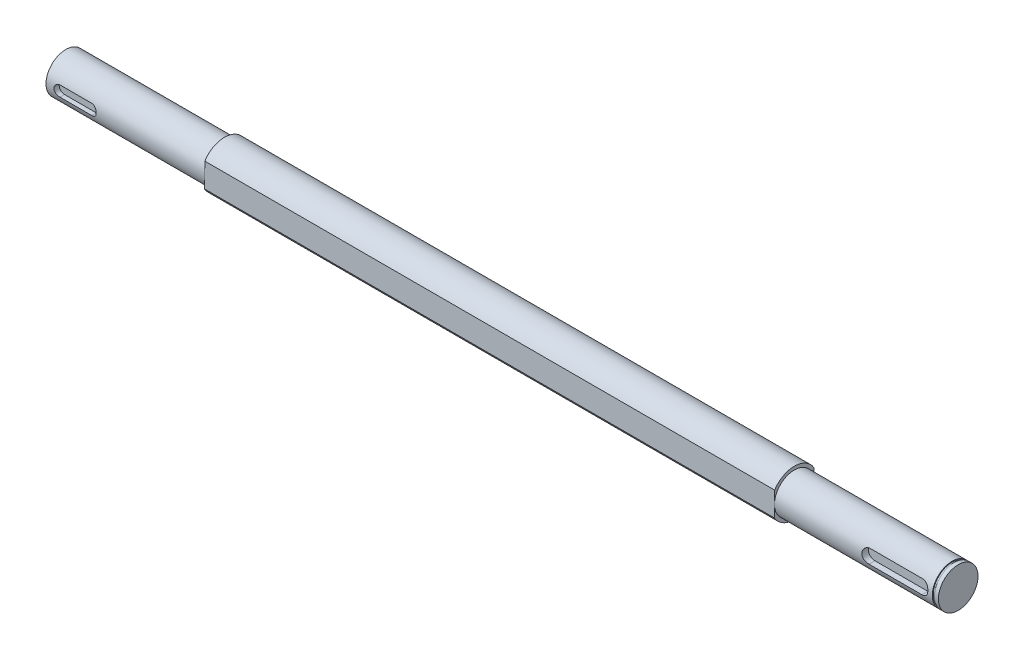
SolidWorks part; units mm, degrees
ref_plane "Ön Düzlem" through (0, 0, 0) normal (0, 0, 1) x (1, 0, 0)
ref_plane "Üst Düzlem" through (0, 0, 0) normal (0, 1, 0) x (1, 0, 0)
ref_plane "Sağ Düzlem" through (0, 0, 0) normal (1, 0, 0) x (0, 0, -1)
sketch "Çizim1" plane through (0, 0, 0) normal (0, 0, 1) x (1, 0, 0)
  line L0 (-337.5, 0) -> (337.5, 0)
  line L1 (-337.5, 0) -> (-337.5, 15)
  line L2 (-337.5, 15) -> (-217.5, 15)
  line L3 (-217.5, 15) -> (-217.5, 17.5)
  line L4 (-217.5, 17.5) -> (213.5, 17.5)
  line L5 (213.5, 17.5) -> (213.5, 15)
  line L6 (213.5, 15) -> (337.5, 15)
  line L7 (337.5, 15) -> (337.5, 0)
  point P2 (0, 0)
  dimension "D1" = 124
  dimension "D2" = 431
  dimension "D3" = 120
  dimension "D4" = 15
  dimension "D5" = 17.5
revolve "Döndür1" add sketch "Çizim1" angle 360 about L0
sketch "Çizim2" plane through (-217.5, 0, 0) normal (-1, 0, 0) x (0, 0, 1)
  line L0 (-14.8439, 9.2687) -> (-15.1517, -8.7564)
  line L1 (0, 0) -> (0, 5.6133) construction
  line L2 (14.8439, 9.2687) -> (15.1517, -8.7564)
  circle A0 centre (0, 0) radius 15 construction
  circle A1 centre (0, 0) radius 17.5 construction
  arc A2 (-14.8439, 9.2687) -> (-15.1517, -8.7564) centre (0, 0) ccw
  arc A3 (14.8439, 9.2687) -> (15.1517, -8.7564) centre (0, 0) cw
extrude "Kes-Ekstrüzyon1" cut sketch "Çizim2" against normal up to surface (431 mm away) up to face at (213.5, 0, 17.5)
ref_plane "Düzlem1" through (0, 0, 15) normal (0, 0, 1) x (1, 0, 0)
sketch "Çizim3" plane through (0, 0, 15) normal (0, 0, 1) x (1, 0, 0)
  line L0 (-327.5, 0) -> (-303.5, 0) construction
  line L1 (-327.5, 4) -> (-303.5, 4)
  line L2 (-327.5, -4) -> (-303.5, -4)
  line L3 (-337.5, 15) -> (-337.5, -15) construction
  arc A0 (-327.5, 4) -> (-327.5, -4) centre (-327.5, 0) ccw
  arc A1 (-303.5, -4) -> (-303.5, 4) centre (-303.5, 0) ccw
  point P3 (-315.5, 0)
  point P8 (-331.5, 0)
  dimension "D1" = 8
  dimension "D2" = 6
  dimension "D3" = 24
extrude "Kes-Ekstrüzyon2" cut sketch "Çizim3" against normal blind 4
sketch "Çizim4" plane through (0, 0, 0) normal (0, 0, 1) x (1, 0, 0)
  line L0 (337.5, 15) -> (213.5, 15) construction
  line L1 (332.9, 15) -> (334.5, 15)
  line L2 (332.9, 15) -> (332.9, 14.3)
  line L3 (332.9, 14.3) -> (334.5, 14.3)
  line L4 (334.5, 15) -> (334.5, 14.3)
  line L5 (337.5, 0) -> (291.1075, 0) construction
  line L6 (337.5, -15) -> (337.5, 15) construction
  dimension "D1" = 28.6
  dimension "D2" = 1.6
  dimension "D3" = 3
revolve "Kes-Döndür1" cut sketch "Çizim4" angle 360 about L5
sketch "Çizim5" plane through (0, 0, 15) normal (0, 0, 1) x (1, 0, 0)
  line L0 (284.5, 1.0735) -> (324.5, 1.0735) construction
  line L1 (284.5, 6.0735) -> (324.5, 6.0735)
  line L2 (284.5, -3.9265) -> (324.5, -3.9265)
  arc A0 (284.5, 6.0735) -> (284.5, -3.9265) centre (284.5, 1.0735) ccw
  arc A1 (324.5, -3.9265) -> (324.5, 6.0735) centre (324.5, 1.0735) ccw
  point P2 (304.5, 1.0735)
  point P7 (329.5, 1.0735)
  dimension "D1" = 10
  dimension "D2" = 8
  dimension "D3" = 40
extrude "Kes-Ekstrüzyon3" cut sketch "Çizim5" against normal blind 5
